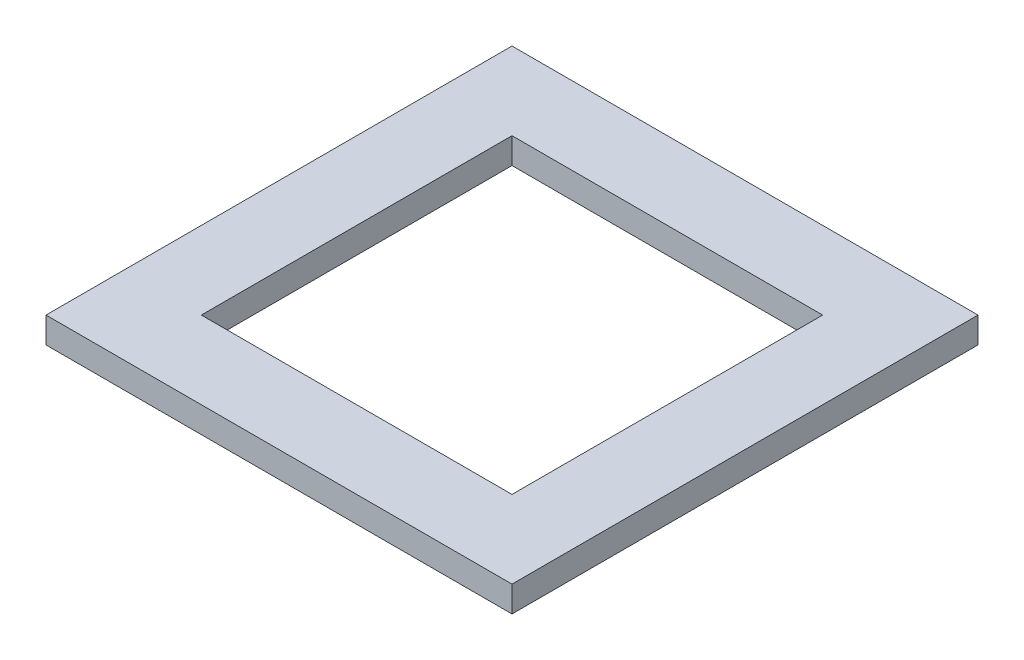
SolidWorks part; units mm, degrees
ref_plane "Front Plane" through (0, 0, 0) normal (0, 0, 1) x (1, 0, 0)
ref_plane "Top Plane" through (0, 0, 0) normal (0, 1, 0) x (1, 0, 0)
ref_plane "Right Plane" through (0, 0, 0) normal (1, 0, 0) x (0, 0, -1)
sketch "Sketch2" plane through (0, 0, 0) normal (0, 1, 0) x (1, 0, 0)
  line L0 (-30, 30) -> (30, 30)
  line L1 (-45, -45) -> (45, -45)
  line L2 (-45, -45) -> (-45, 45)
  line L3 (-45, 45) -> (45, 45)
  line L4 (45, -45) -> (45, 45)
  line L5 (-45, -45) -> (45, 45) construction
  line L6 (-45, 45) -> (45, -45) construction
  line L7 (30, -30) -> (30, 30)
  line L8 (-30, -30) -> (30, -30)
  line L9 (-30, -30) -> (-30, 30)
  point P0 (0, 0)
  dimension "D1" = 90
  dimension "D2" = 90
  dimension "D3" = 15
extrude "Boss-Extrude1" add sketch "Sketch2" along normal blind 5
